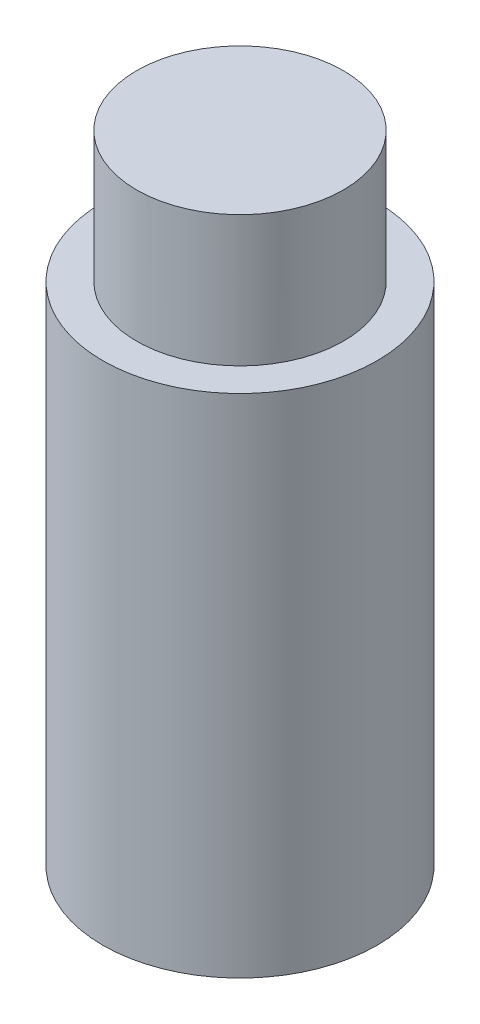
SolidWorks part; units mm, degrees
ref_plane "前基準面" through (0, 0, 0) normal (0, 0, 1) x (1, 0, 0)
ref_plane "上基準面" through (0, 0, 0) normal (0, 1, 0) x (1, 0, 0)
ref_plane "右基準面" through (0, 0, 0) normal (1, 0, 0) x (0, 0, -1)
sketch "草圖1" plane through (0, 0, 0) normal (0, 1, 0) x (1, 0, 0)
  circle A0 centre (0, 0) radius 2.92
extrude "填料-伸長1" add sketch "草圖1" along normal blind 18
sketch "草圖2" plane through (0, 0, 0) normal (0, -1, 0) x (1, 0, 0)
  circle A0 centre (0, 0) radius 3.8742
extrude "填料-伸長3" add sketch "草圖2" against normal blind 14.3
